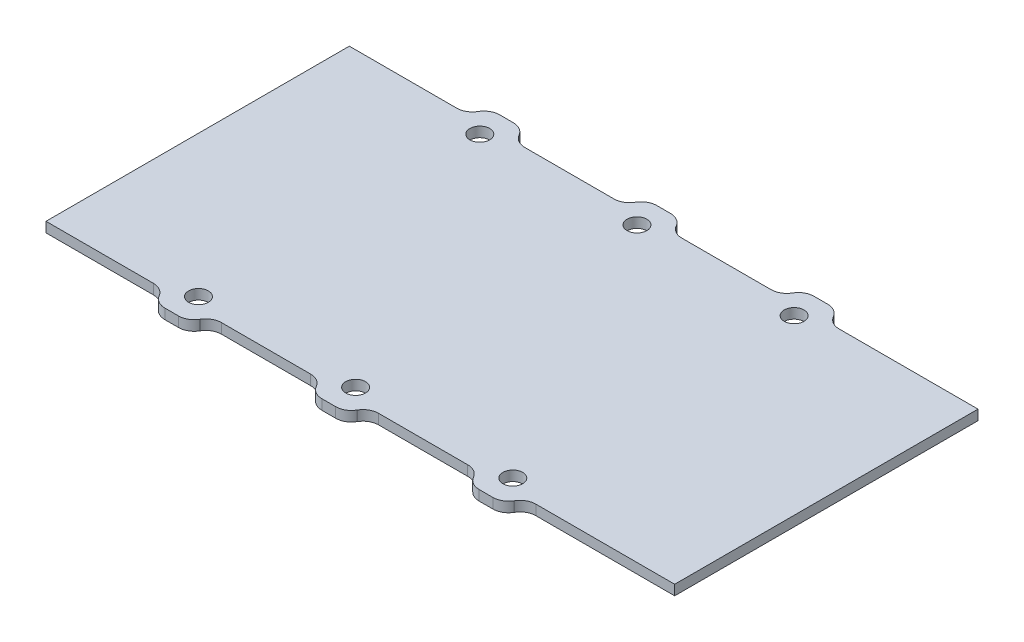
SolidWorks part; units mm, degrees
ref_plane "Front" through (0, 0, 0) normal (0, 0, 1) x (1, 0, 0)
ref_plane "Top" through (0, 0, 0) normal (0, 1, 0) x (1, 0, 0)
ref_plane "Right" through (0, 0, 0) normal (1, 0, 0) x (0, 0, -1)
sketch "Sketch1" plane through (0, 0, 0) normal (0, 1, 0) x (1, 0, 0)
  line L0 (-27.5, 24.125) -> (-27.5, -24.125) construction
  line L1 (-50, 24.125) -> (-32.9155, 24.125)
  line L2 (-50, 24.125) -> (-50, -24.125)
  line L3 (-50, -24.125) -> (-32.9155, -24.125)
  line L4 (50, 24.125) -> (50, -24.125)
  line L5 (-50, 24.125) -> (50, -24.125) construction
  line L6 (-50, -24.125) -> (50, 24.125) construction
  line L7 (-24.2283, -25.3388) -> (-24.2717, -25.4112)
  line L8 (-30.7717, -25.3388) -> (-30.7283, -25.4112)
  line L9 (-26.4155, -26.625) -> (-28.5845, -26.625)
  line L10 (-22.0845, -24.125) -> (-7.9155, -24.125)
  line L11 (-50, 0) -> (50, 0) construction
  line L12 (-5, 0) -> (-105, 0) construction
  line L13 (-26.4155, 26.625) -> (-28.5845, 26.625)
  line L14 (-22.0845, 24.125) -> (-7.9155, 24.125)
  line L15 (-1.4155, 26.625) -> (-3.5845, 26.625)
  line L16 (-1.4155, -26.625) -> (-3.5845, -26.625)
  line L17 (23.5845, 26.625) -> (21.4155, 26.625)
  line L18 (23.5845, -26.625) -> (21.4155, -26.625)
  line L19 (0.7717, 25.3388) -> (0.7283, 25.4112)
  line L20 (27.9155, -24.125) -> (50, -24.125)
  line L21 (2.9155, -24.125) -> (17.0845, -24.125)
  line L22 (2.9155, 24.125) -> (17.0845, 24.125)
  line L23 (27.9155, 24.125) -> (50, 24.125)
  line L24 (-30.7283, 25.4112) -> (-30.7717, 25.3388)
  line L25 (-24.2283, 25.3388) -> (-24.2717, 25.4112)
  line L28 (-5.7283, 25.4112) -> (-5.7717, 25.3388)
  line L29 (25.7717, 25.3388) -> (25.7283, 25.4112)
  line L30 (19.2283, 25.3388) -> (19.2717, 25.4112)
  line L31 (25.7717, -25.3388) -> (25.7283, -25.4112)
  line L32 (19.2717, -25.4112) -> (19.2283, -25.3388)
  line L33 (-5.7283, -25.4112) -> (-5.7717, -25.3388)
  line L34 (0.7283, -25.4112) -> (0.7717, -25.3388)
  circle A0 centre (-27.5, -22.375) radius 2.8 construction
  circle A1 centre (-27.5, -22.375) radius 1.575
  arc A2 (-30.7283, -25.4112) -> (-28.5845, -26.625) centre (-28.5845, -24.125) ccw
  arc A3 (-24.2717, -25.4112) -> (-26.4155, -26.625) centre (-26.4155, -24.125) cw
  arc A4 (-30.7717, -25.3388) -> (-32.9155, -24.125) centre (-32.9155, -26.625) ccw
  arc A5 (-24.2283, -25.3388) -> (-22.0845, -24.125) centre (-22.0845, -26.625) cw
  circle A6 centre (-27.5, 22.375) radius 2.8 construction
  circle A7 centre (-27.5, 22.375) radius 1.575
  arc A8 (-30.7717, 25.3388) -> (-32.9155, 24.125) centre (-32.9155, 26.625) cw
  arc A9 (-30.7283, 25.4112) -> (-28.5845, 26.625) centre (-28.5845, 24.125) cw
  arc A10 (-24.2717, 25.4112) -> (-26.4155, 26.625) centre (-26.4155, 24.125) ccw
  arc A11 (-24.2283, 25.3388) -> (-22.0845, 24.125) centre (-22.0845, 26.625) ccw
  arc A12 (0.7717, 25.3388) -> (2.9155, 24.125) centre (2.9155, 26.625) ccw
  arc A13 (0.7283, 25.4112) -> (-1.4155, 26.625) centre (-1.4155, 24.125) ccw
  arc A14 (-5.7283, 25.4112) -> (-3.5845, 26.625) centre (-3.5845, 24.125) cw
  arc A15 (-5.7717, 25.3388) -> (-7.9155, 24.125) centre (-7.9155, 26.625) cw
  circle A16 centre (-2.5, 22.375) radius 1.575
  arc A17 (0.7717, -25.3388) -> (2.9155, -24.125) centre (2.9155, -26.625) cw
  arc A18 (0.7283, -25.4112) -> (-1.4155, -26.625) centre (-1.4155, -24.125) cw
  arc A19 (-5.7283, -25.4112) -> (-3.5845, -26.625) centre (-3.5845, -24.125) ccw
  arc A20 (-5.7717, -25.3388) -> (-7.9155, -24.125) centre (-7.9155, -26.625) ccw
  circle A21 centre (-2.5, -22.375) radius 1.575
  arc A22 (25.7717, 25.3388) -> (27.9155, 24.125) centre (27.9155, 26.625) ccw
  arc A23 (25.7283, 25.4112) -> (23.5845, 26.625) centre (23.5845, 24.125) ccw
  arc A24 (19.2717, 25.4112) -> (21.4155, 26.625) centre (21.4155, 24.125) cw
  arc A25 (19.2283, 25.3388) -> (17.0845, 24.125) centre (17.0845, 26.625) cw
  circle A26 centre (22.5, 22.375) radius 1.575
  arc A27 (25.7717, -25.3388) -> (27.9155, -24.125) centre (27.9155, -26.625) cw
  arc A28 (25.7283, -25.4112) -> (23.5845, -26.625) centre (23.5845, -24.125) cw
  arc A29 (19.2717, -25.4112) -> (21.4155, -26.625) centre (21.4155, -24.125) ccw
  arc A30 (19.2283, -25.3388) -> (17.0845, -24.125) centre (17.0845, -26.625) ccw
  circle A31 centre (22.5, -22.375) radius 1.575
  point P0 (0, 0)
  point P12 (-27.5, -26.625)
  point P18 (-30, -26.625)
  point P21 (-25, -26.625)
  point P24 (-31.5, -24.125)
  point P27 (-23.5, -24.125)
  point P47 (-2.5, 26.625)
  point P105 (-27.5, 26.625)
  dimension "D7" = 5.6
  dimension "D8" = 3.15
  dimension "D9" = 2.5
  dimension "D1" = 48.25
  dimension "D2" = 100
  dimension "D3" = 22.5
  dimension "D4" = 2.5
  dimension "D5" = 8
  dimension "D6" = 5
  dimension "D10" = 1.75
  dimension "D12" = 25
  dimension "D11" = 3
extrude "Boss-Extrude1" add sketch "Sketch1" along normal blind 1.6
equation "\"D3@Sketch1\"=10+25/2"
